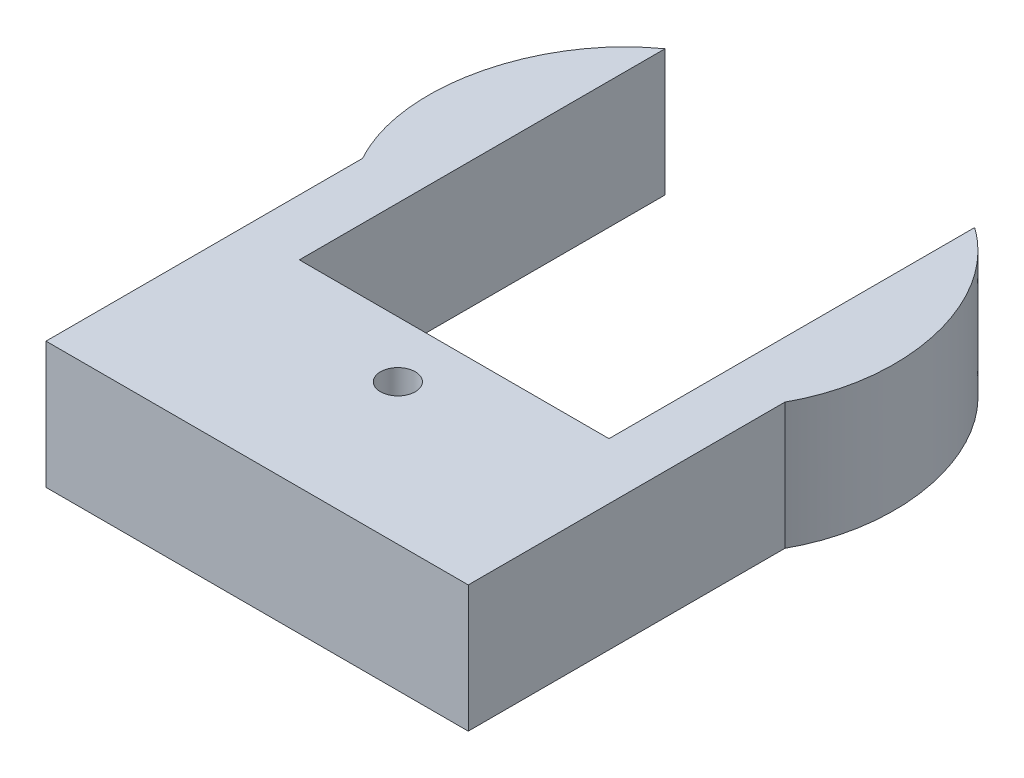
SolidWorks part; units mm, degrees
ref_plane "Front Plane" through (0, 0, 0) normal (0, 0, 1) x (1, 0, 0)
ref_plane "Top Plane" through (0, 0, 0) normal (0, 1, 0) x (1, 0, 0)
ref_plane "Right Plane" through (0, 0, 0) normal (1, 0, 0) x (0, 0, -1)
sketch "Sketch1" plane through (0, 0, 0) normal (0, 1, 0) x (1, 0, 0)
  line L0 (8, 67.5015) -> (8, 79.9541)
  line L1 (0, 0) -> (60, 0)
  line L2 (0, 0) -> (0, 28)
  line L3 (8, 28) -> (52, 28)
  line L4 (60, 0) -> (60, 28)
  line L6 (0, 28) -> (0, 45)
  line L8 (8, 28) -> (8, 67.5015)
  line L10 (60, 28) -> (60, 45)
  line L12 (52, 28) -> (52, 70.2973)
  line L13 (30, 28) -> (30, 82.123) construction
  line L14 (52, 70.2973) -> (52, 79.9541)
  arc A0 (11.5, 82) -> (0, 45) centre (24.25, 57.75) ccw construction
  spline S0 degree 3 poles (0, 45) (-4.2674, 52.7022) (-3.8497, 67.2321) (4.5722, 77.5249) (8, 79.9541) knots 0 0 0 0 0.616859 0.907352 0.907352 0.907352 0.907352
  spline S1 degree 3 poles (60, 45) (64.2674, 52.7022) (63.8497, 67.2321) (55.4278, 77.5249) (52, 79.9541) knots 0 0 0 0 0.616859 0.907352 0.907352 0.907352 0.907352
  dimension "D1" = 60
  dimension "D2" = 28
extrude "Boss-Extrude1" add sketch "Sketch1" along normal blind 18
sketch "Sketch3" plane through (0, 0, 0) normal (0, -1, 0) x (1, 0, 0)
  circle A0 centre (30, -20) radius 2.4697
extrude "Cut-Extrude1" cut sketch "Sketch3" against normal blind 21
